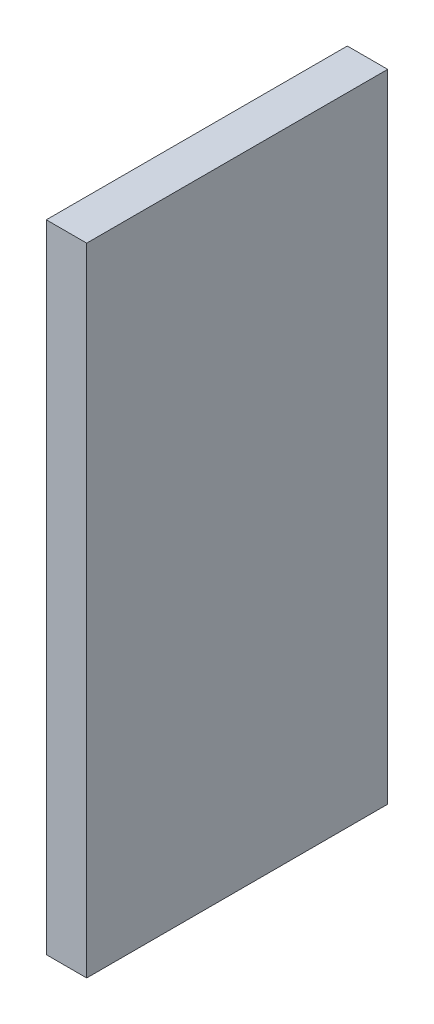
SolidWorks part; units mm, degrees
ref_plane "Front Plane" through (0, 0, 0) normal (0, 0, 1) x (1, 0, 0)
ref_plane "Top Plane" through (0, 0, 0) normal (0, 1, 0) x (1, 0, 0)
ref_plane "Right Plane" through (0, 0, 0) normal (1, 0, 0) x (0, 0, -1)
sketch "Sketch1" plane through (0, 0, 0) normal (1, 0, 0) x (0, 0, -1)
  line L1 (0, 0) -> (47.3, 0)
  line L2 (0, 0) -> (0, 100)
  line L3 (0, 100) -> (47.3, 100)
  line L4 (47.3, 0) -> (47.3, 100)
  dimension "D1" = 47.3
  dimension "D2" = 100
extrude "Boss-Extrude1" add sketch "Sketch1" along normal blind 6.35
